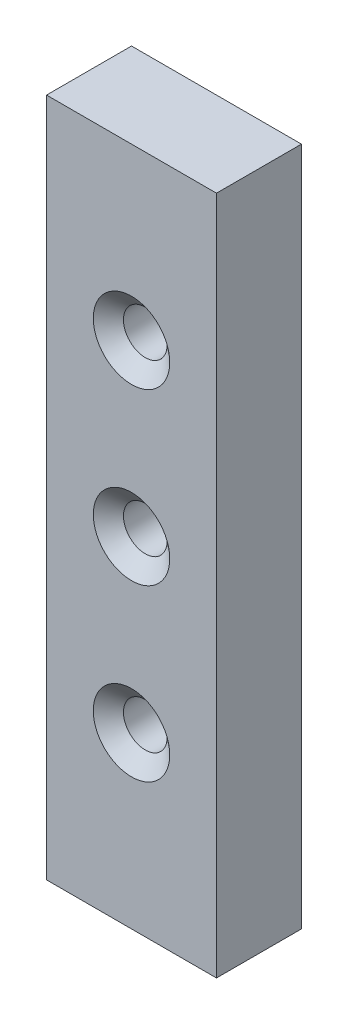
SolidWorks part; units mm, degrees
ref_plane "Front Plane" through (0, 0, 0) normal (0, 0, 1) x (1, 0, 0)
ref_plane "Top Plane" through (0, 0, 0) normal (0, 1, 0) x (1, 0, 0)
ref_plane "Right Plane" through (0, 0, 0) normal (1, 0, 0) x (0, 0, -1)
sketch "Sketch1" plane through (0, 0, 0) normal (0, 0, 1) x (1, 0, 0)
  line L1 (-6.35, 25.4) -> (6.35, 25.4)
  line L2 (-6.35, 25.4) -> (-6.35, -25.4)
  line L3 (-6.35, -25.4) -> (6.35, -25.4)
  line L4 (6.35, 25.4) -> (6.35, -25.4)
  dimension "D1" = 6.35
  dimension "D2" = 12.7
  dimension "D3" = 25.4
  dimension "D4" = 50.8
extrude "Boss-Extrude1" add sketch "Sketch1" along normal mid plane 6.35
sketch "Sketch5" plane through (0, 0, 3.175) normal (0, 0, 1) x (1, 0, 0)
  line L0 (6.35, 25.4) -> (-6.35, 25.4) construction
  line L1 (-6.35, 25.4) -> (-6.35, -25.4) construction
  point P0 (0, 12.7)
  point P11 (0, 0)
  point P12 (0, -12.7)
  dimension "D1" = 12.7
  dimension "D2" = 6.35
  dimension "D3" = 1
  dimension "D4" = 3
hole_wizard "CSK for #4 Flat Head Machine Screw (100)1" positions "Sketch7" profile "Sketch6" countersink size "#4" standard "ANSI Inch" end condition through all
sketch "Sketch7" plane through (0, 0, 3.175) normal (0, 0, 1) x (1, 0, 0)
  line L0 (6.35, 25.4) -> (-6.35, 25.4) construction
  point P0 (0, 12.7)
  point P3 (0, 0)
  point P6 (0, -12.7)
  point P11 (0, 25.4)
  point P14 (0, 0)
sketch "Sketch6" plane through (0, 12.7, 3.175) normal (1, 0, 0) x (0, -1, 0)
  line L0 (0, 0) -> (0, 6.35)
  line L1 (0, 6.35) -> (1.6319, 6.35)
  line L2 (1.6319, 6.35) -> (1.6319, 1.0284)
  line L3 (1.6319, 1.0284) -> (2.8575, 0)
  line L5 (2.8575, 0) -> (0, 0)
  line L6 (-1.6319, 1.0284) -> (-2.8575, 0) construction
  line L11 (0, -6.35) -> (0, 107.95) construction
  dimension "Thru Hole Dia." = 3.2639
  dimension "Thru Hole Depth" = 6.35
  dimension "Near C'Sink Dia." = 5.715
  dimension "Near C'Sink Angle" = 100
